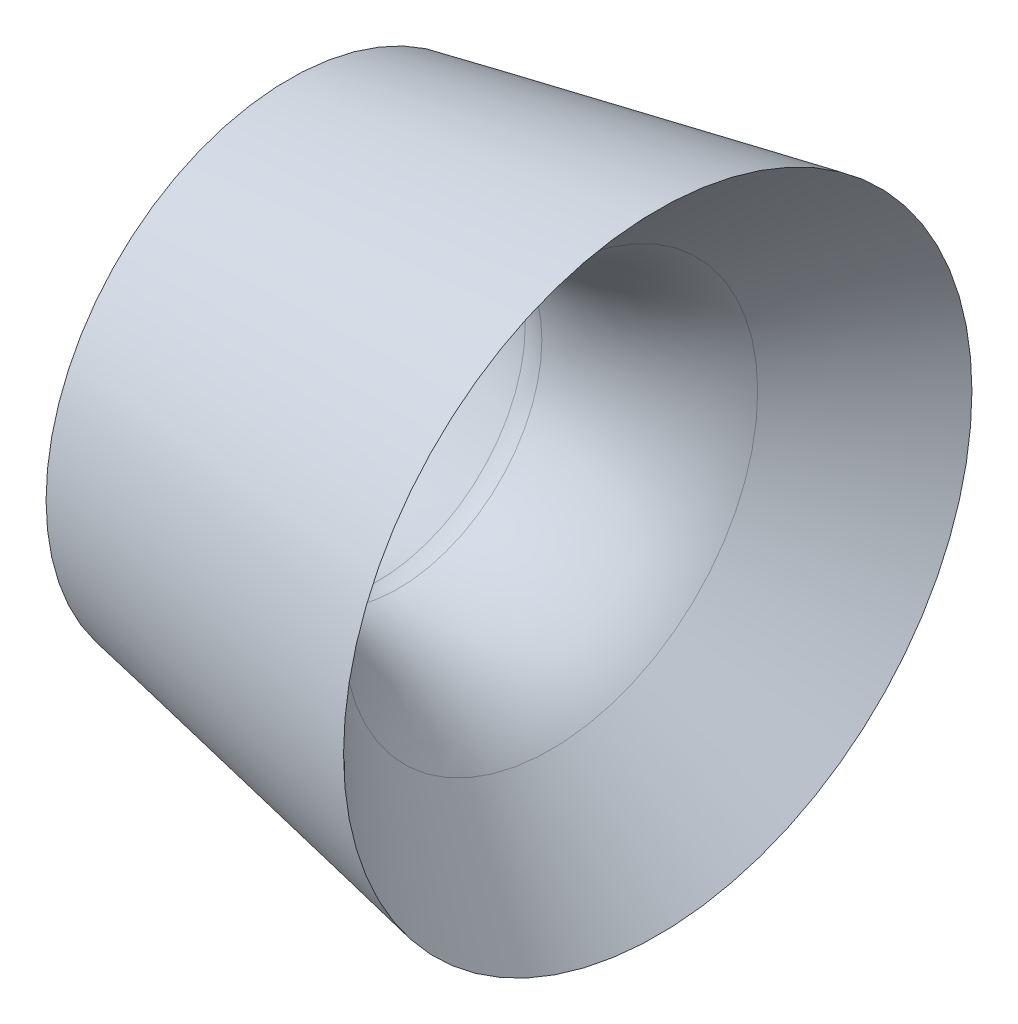
SolidWorks part; units mm, degrees
material "C (Graphite)"
ref_plane "Front Plane" through (0, 0, 0) normal (0, 0, 1) x (1, 0, 0)
ref_plane "Top Plane" through (0, 0, 0) normal (0, 1, 0) x (1, 0, 0)
ref_plane "Right Plane" through (0, 0, 0) normal (1, 0, 0) x (0, 0, -1)
sketch "Sketch1" plane through (0, 0, 0) normal (0, 0, 1) x (1, 0, 0)
  line L1 (0, 24.472) -> (-8.3426, 16.1295)
  line L3 (0, 0) -> (-30, 0) construction
  line L5 (-30, 18.6909) -> (-30, 14.6909) construction
  line L6 (-30, 18.6909) -> (-28.7014, 18.9412) construction
  line L8 (0, 24.472) -> (-30, 24.472) construction
  line L10 (0, 24.472) -> (0, 0) construction
  line L11 (-28.7014, 18.9412) -> (-28.7014, 14.2061)
  line L12 (-28.7014, 18.9412) -> (0, 24.472)
  arc A1 (-8.3426, 16.1295) -> (-20.2285, 11.2061) centre (-20.2285, 28.0154) cw
  arc A2 (-20.2285, 11.2061) -> (-21.8411, 11.5215) centre (-20.2285, 15.4869) cw
  arc A4 (-21.8411, 11.5215) -> (-28.7014, 14.2061) centre (-126.69, -246.3001) ccw
  arc A5 (-28.7014, 14.2061) -> (-30, 14.6909) centre (-126.69, -246.3001) ccw construction
  dimension "D11" = 4.2807
  dimension "D12" = 16.8092
  dimension "D4" = 278.3258
  dimension "D6" = 4
  dimension "D20" = 30
  dimension "D3" = 10.907
  dimension "D5" = 24.472
  dimension "D7" = 11.2061
  dimension "D8" = 3
  dimension "D9" = 45
  dimension "D15" = 22.13
revolve "Revolve1" add sketch "Sketch1" angle 360 about L3
equation "\"theta_t\"= 36.9009 - ( 426.271 / ( \"Aet\" + 7.00037 ) ) + ( 10026.8 / ( \"Aet\" + 7.00037 ) ^ 2 ) - ( 175410 / ( \"Aet\" + 7.00037 ) ^ 3 ) + ( ( 1.6742 * ( 10 ^ 6 ) ) / ( \"Aet\" + 7.00037 ) ^ 4 ) - ( ( 6.7643 * ( 10 ^ 6 ) ) / ( \"Aet\" + 7.00037 ) ^ 5 )"
equation "\"rt\"= ( 0.022412299 / 2 ) * 1000"
equation "\"re\"= sqr ( \"rt\" ^ 2 * \"Aet\" )"
equation "\"Aet\"= 4.317"
equation "\"L\"= 0.8 * ( ( \"re\" / tan ( 15 ) ) - ( \"rt\" / tan ( 15 ) ) )"
equation "\"lc\"= ( \"l*\" / \"cr\" )"
equation "\"b\"= tan ( \"theta_t\" )"
equation "\"a\"= ( \"re\" - \"b\" * \"L\" - \"c\" ) / \"L\" ^ 2"
equation "\"D11@Sketch1\"=0.382*\"rt\""
equation "\"D12@Sketch1\"=1.5*\"rt\""
equation "\"c\"= \"rt\" * ( 1.382 - 0.382 * cos ( \"theta_t\" ) )"
equation "\"D15@Sketch1\"=\"theta_t\""
equation "\"cr\"= 5.978857531"
equation "\"rc\"= sqr ( \"cr\" * ( \"rt\" ^ 2 ) )"
equation "\"l*\"= 1000"
equation "\"th\"= 10"
equation "\"theta_cr\"= 45deg"
equation "\"D9@Sketch1\"=\"theta_cr\""
